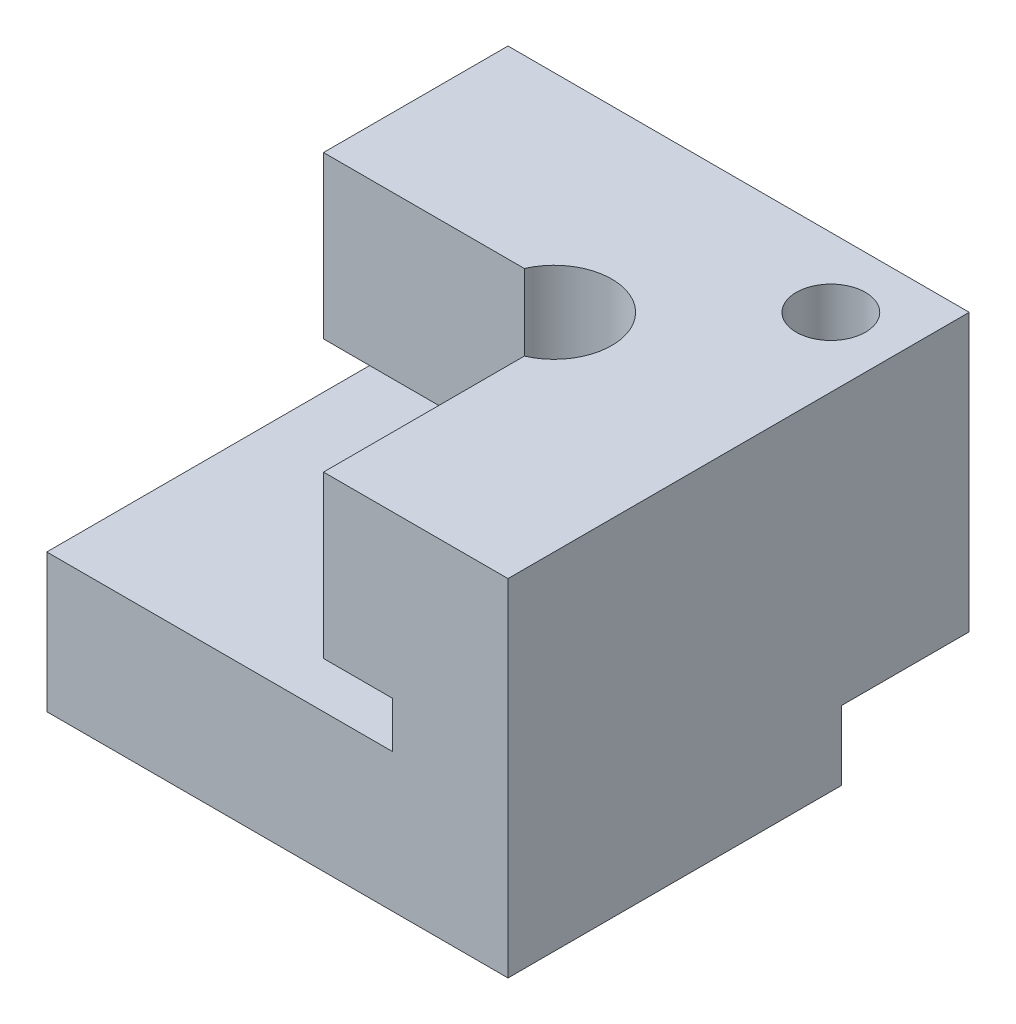
SolidWorks part; units mm, degrees
ref_plane "Front Plane" through (0, 0, 0) normal (0, 0, 1) x (1, 0, 0)
ref_plane "Top Plane" through (0, 0, 0) normal (0, 1, 0) x (1, 0, 0)
ref_plane "Right Plane" through (0, 0, 0) normal (1, 0, 0) x (0, 0, -1)
sketch "Sketch1" plane through (0, 0, 0) normal (0, 1, 0) x (1, 0, 0)
  line L1 (0, 0) -> (20, 0)
  line L2 (0, 0) -> (0, 20)
  line L3 (0, 20) -> (20, 20)
  line L4 (20, 0) -> (20, 20)
  dimension "D1" = 20
  dimension "D2" = 20
extrude "Boss-Extrude1" add sketch "Sketch1" along normal blind 15
sketch "Sketch2" plane through (0, 15, 0) normal (0, 1, 0) x (1, 0, 0)
  line L1 (0, 0) -> (12, 0)
  line L2 (0, 0) -> (0, 12)
  line L3 (0, 12) -> (12, 12)
  line L4 (12, 0) -> (12, 12)
  dimension "D1" = 12
  dimension "D2" = 12
extrude "Cut-Extrude1" cut sketch "Sketch2" against normal blind 9
sketch "Sketch3" plane through (0, 0, 0) normal (0, 0, 1) x (1, 0, 0)
  line L1 (12, 6) -> (15, 6)
  line L2 (12, 6) -> (12, 8)
  line L3 (12, 8) -> (15, 8)
  line L4 (15, 6) -> (15, 8)
  point P5 (12, 7)
  dimension "D1" = 3
  dimension "D2" = 2
extrude "Cut-Extrude2" cut sketch "Sketch3" against normal blind 15
sketch "Sketch4" plane through (0, 0, 0) normal (-1, 0, 0) x (0, 0, 1)
  line L1 (-12, 6) -> (-15, 6)
  line L2 (-12, 6) -> (-12, 8)
  line L3 (-12, 8) -> (-15, 8)
  line L4 (-15, 6) -> (-15, 8)
  dimension "D1" = 3
  dimension "D2" = 2
extrude "Cut-Extrude3" cut sketch "Sketch4" against normal blind 15
sketch "Sketch5" plane through (0, 15, 0) normal (0, 1, 0) x (1, 0, 0)
  line L0 (12, 0) -> (20, 0) construction
  line L1 (0, 20) -> (0, 12) construction
  circle A0 centre (11, 11) radius 1.5
  circle A1 centre (17, 17) radius 1.5
  dimension "D1" = 17
  dimension "D2" = 17
  dimension "D3" = 11
  dimension "D4" = 11
  dimension "D5" = 3
  dimension "D6" = 3
extrude "Cut-Extrude4" cut sketch "Sketch5" against normal blind 15
sketch "Sketch6" plane through (0, 15, 0) normal (0, 1, 0) x (1, 0, 0)
  circle A0 centre (11, 11) radius 2.5
  dimension "D1" = 5
extrude "Cut-Extrude5" cut sketch "Sketch6" against normal blind 12
sketch "Sketch7" plane through (0, 0, 0) normal (0, -1, 0) x (-1, 0, 0)
  line L0 (-20, 0) -> (-20, 20) construction
  line L1 (-19.1, 14.7196) -> (-16.0752, 14.0412)
  line L2 (-16.0752, 14.0412) -> (-13.9752, 16.3215)
  line L3 (-13.9752, 16.3215) -> (-14.9, 19.2804)
  line L4 (-14.9, 19.2804) -> (-17.9248, 19.9588)
  line L5 (-17.9248, 19.9588) -> (-20.0248, 17.6785)
  line L6 (-20.0248, 17.6785) -> (-19.1, 14.7196)
  circle A0 centre (-17, 17) radius 2.6847 construction
  dimension "D1" = 3.1
  dimension "D2" = 0.9
extrude "Cut-Extrude6" cut sketch "Sketch7" against normal blind 3
sketch "Sketch8" plane through (0, 0, 0) normal (0, -1, 0) x (-1, 0, 0)
  line L0 (-20, 20) -> (0, 20) construction
  line L1 (-20, 14.7196) -> (-19.1, 14.7196)
  line L2 (-20, 14.7196) -> (-20, 20)
  line L3 (-20, 20) -> (-14.9, 20)
  line L4 (-14.9, 19.2804) -> (-14.9, 20)
  line L5 (-20, 17.7055) -> (-20, 20) construction
  line L7 (-14.9, 19.2804) -> (-19.1, 14.7196)
  dimension "D1" = 0
  dimension "D2" = 0
  dimension "D3" = 0
  dimension "D4" = 0
extrude "Cut-Extrude7" cut sketch "Sketch8" against normal blind 3
sketch "Sketch9" plane through (0, 0, 0) normal (0, -1, 0) x (-1, 0, 0)
  line L1 (-13.6735, 16.297) -> (-14.7279, 19.5293)
  line L3 (-18.0544, 20.2324) -> (-20.3265, 17.703)
  line L5 (-19.2721, 14.4707) -> (-15.9456, 13.7676)
  line L6 (-15.9456, 13.7676) -> (-13.6735, 16.297)
  line L7 (-19.2721, 14.4707) -> (-20.9448, 14.4707)
  line L8 (-20.9448, 14.4707) -> (-20.3265, 17.703)
  line L9 (-14.7279, 19.5293) -> (-14.7279, 20)
  line L10 (-14.9, 20) -> (0, 20) construction
  line L11 (-14.7279, 20) -> (-18.0544, 20.2324)
  line L13 (-16.3912, 19.8809) -> (-18.0544, 20.2324) [skipped]
  line L14 (-19.7993, 16.0868) -> (-19.2721, 14.4707) [skipped]
  dimension "D1" = 3.4
extrude "Cut-Extrude8" cut sketch "Sketch9" against normal blind 3
